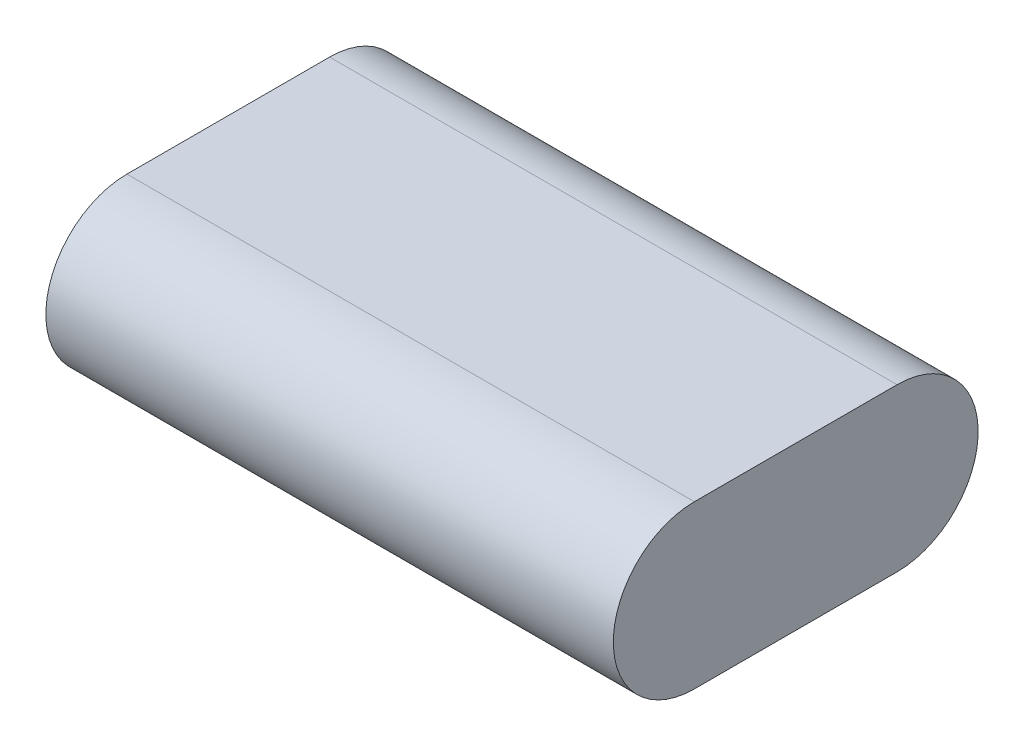
SolidWorks part; units mm, degrees
ref_plane "Front Plane" through (0, 0, 0) normal (0, 0, 1) x (1, 0, 0)
ref_plane "Top Plane" through (0, 0, 0) normal (0, 1, 0) x (1, 0, 0)
ref_plane "Right Plane" through (0, 0, 0) normal (1, 0, 0) x (0, 0, -1)
sketch "Sketch1" plane through (0, 0, 0) normal (1, 0, 0) x (0, 0, -1)
  line L1 (0, 0) -> (5, 0)
  line L3 (0, 4) -> (5, 4)
  arc A0 (0, 4) -> (0, 0) centre (0, 2) ccw
  arc A1 (5, 0) -> (5, 4) centre (5, 2) ccw
  point P5 (0, 2)
  dimension "D1" = 4
  dimension "D2" = 9
extrude "Boss-Extrude1" add sketch "Sketch1" along normal blind 14
